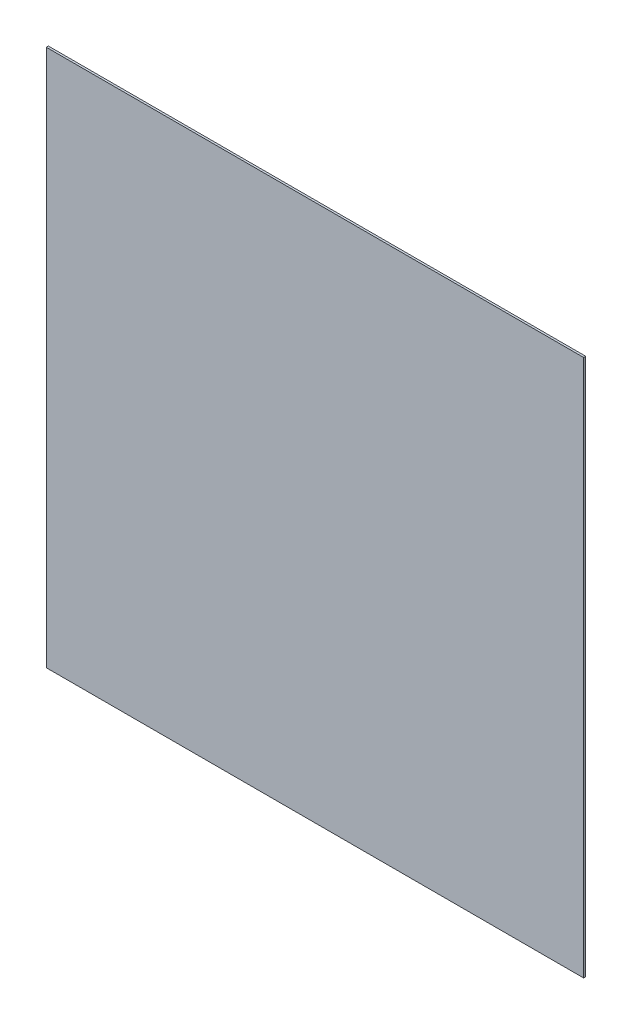
SolidWorks part; units mm, degrees
ref_plane "Front Plane" through (0, 0, 0) normal (0, 0, 1) x (1, 0, 0)
ref_plane "Top Plane" through (0, 0, 0) normal (0, 1, 0) x (1, 0, 0)
ref_plane "Right Plane" through (0, 0, 0) normal (1, 0, 0) x (0, 0, -1)
sketch "Sketch1" plane through (0, 0, 0) normal (0, 0, 1) x (1, 0, 0)
  line L1 (-413.3684, 286.386) -> (356.6316, 286.386)
  line L2 (-413.3684, 286.386) -> (-413.3684, -483.614)
  line L3 (-413.3684, -483.614) -> (356.6316, -483.614)
  line L4 (356.6316, 286.386) -> (356.6316, -483.614)
  dimension "D1" = 770
  dimension "D2" = 770
extrude "Boss-Extrude1" add sketch "Sketch1" along normal blind 3
